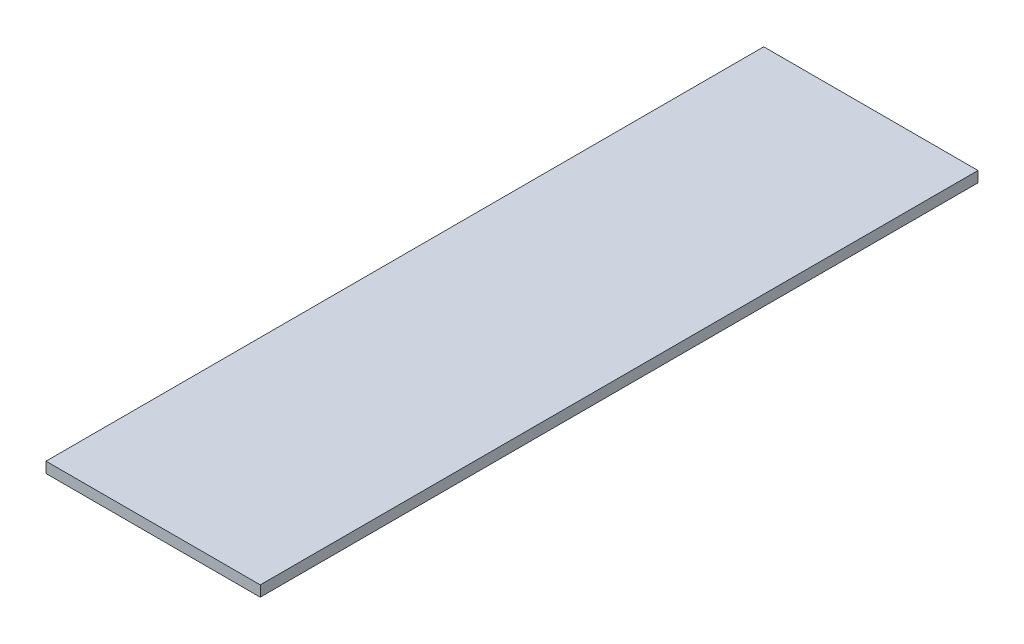
SolidWorks part; units mm, degrees
ref_plane "Front Plane" through (0, 0, 0) normal (0, 0, 1) x (1, 0, 0)
ref_plane "Top Plane" through (0, 0, 0) normal (0, 1, 0) x (1, 0, 0)
ref_plane "Right Plane" through (0, 0, 0) normal (1, 0, 0) x (0, 0, -1)
sketch "Sketch1" plane through (0, 0, 0) normal (0, 1, 0) x (1, 0, 0)
  line L1 (0, 0) -> (63.5, 0)
  line L2 (0, 0) -> (0, 212.725)
  line L3 (0, 212.725) -> (63.5, 212.725)
  line L4 (63.5, 0) -> (63.5, 212.725)
  dimension "D1" = 212.725
  dimension "D2" = 63.5
extrude "Boss-Extrude1" add sketch "Sketch1" along normal blind 3.175
